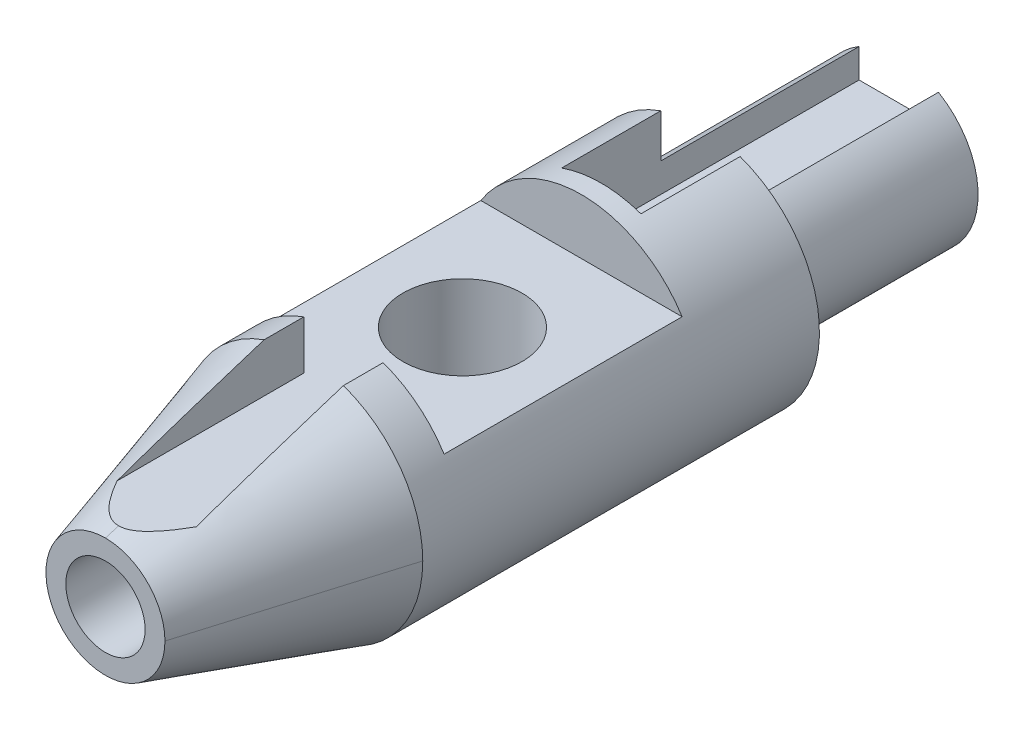
SolidWorks part; units mm, degrees
ref_plane "Front Plane" through (0, 0, 0) normal (0, 0, 1) x (1, 0, 0)
ref_plane "Top Plane" through (0, 0, 0) normal (0, 1, 0) x (1, 0, 0)
ref_plane "Right Plane" through (0, 0, 0) normal (1, 0, 0) x (0, 0, -1)
sketch "Sketch2" plane through (0, 0, 0) normal (0, 0, 1) x (1, 0, 0)
  circle A0 centre (0, 0) radius 30
  dimension "D1" = 60
extrude "Boss-Extrude1" add sketch "Sketch2" against normal blind 50
sketch "Sketch4" plane through (0, 0, -50) normal (0, 0, -1) x (-1, 0, 0)
  circle A0 centre (0, 0) radius 30
  dimension "D1" = 60
extrude "Boss-Extrude4" add sketch "Sketch4" along normal blind 100 contours A0
sketch "Sketch8" plane through (0, 0, -150) normal (0, 0, -1) x (-1, 0, 0)
  circle A1 centre (0, 0) radius 20
  dimension "D2" = 40
sketch "Sketch11" plane through (0, 0, 0) normal (1, 0, 0) x (0, 0, -1)
  line L0 (0, 15) -> (50, 30)
  line L1 (0, 30) -> (0, -30) construction
  line L2 (50, 30) -> (0, 30)
  line L3 (0, 30) -> (0, 15)
  line L4 (150, 30) -> (0, 30) construction
  line L5 (-75, 0) -> (75, 0) construction
  dimension "D1" = 15
  dimension "D2" = 50
  dimension "D3" = 150
sweep "Cut-Sweep1" cut profiles "Sketch11" path edge at (30, 0, 0)
sketch "Sketch20" plane through (0, 0, 0) normal (1, 0, 0) x (0, 0, -1)
  line L0 (60, 30) -> (60, 16)
  line L1 (150, 30) -> (50, 30) construction
  line L2 (60, 16) -> (120, 16)
  line L3 (120, 16) -> (120, 30)
  line L4 (120, 30) -> (60, 30)
  line L5 (50, 30) -> (50, 0) construction
  line L6 (70, -30) -> (110, -30)
  line L7 (50, -30) -> (150, -30) construction
  line L8 (110, -30) -> (110, -20)
  line L9 (110, -20) -> (70, -20)
  line L10 (70, -20) -> (70, -30)
  line L11 (50, -30) -> (50, 30) construction
  dimension "D1" = 60
  dimension "D2" = 10
  dimension "D3" = 14
  dimension "D4" = 40
  dimension "D5" = 20
  dimension "D6" = 10
extrude "Cut-Extrude3" cut sketch "Sketch20" against normal up to next and the other way up to next contours L4 L0 L2 L3 | L10 L6 L8 L9
extrude "Boss-Extrude6" add sketch "Sketch8" along normal blind 50
sketch "Sketch22" plane through (0, 16, 0) normal (0, 1, 0) x (1, 0, 0)
  line L0 (-10, 60) -> (-10, 0)
  line L1 (-10, 0) -> (10, 0)
  line L2 (10, 0) -> (10, 60)
  line L3 (10, 60) -> (-10, 60)
  line L9 (25.3772, 60) -> (-25.3772, 60) construction
  dimension "D1" = 20
  dimension "D2" = 10
extrude "Cut-Extrude14" cut sketch "Sketch22" along normal up to next contours L0 L1 L2 L3
sketch3d "3DSketch1"
  point P4 (0, 10, 0)
  point P13 (0, 10, -200)
ref_plane "Plane3" through (0, 10, 0) normal (0, 1, 0) x (1, 0, 0)
sketch "Sketch23" plane through (0, 10, 0) normal (0, 1, 0) x (1, 0, 0)
  line L0 (-10, 200) -> (10, 200)
  line L1 (20, 200) -> (-20, 200) construction
  line L2 (10, 200) -> (10, 125)
  line L3 (10, 125) -> (-10, 125)
  line L4 (-10, 125) -> (-10, 200)
  line L5 (0, 0) -> (0, 3.3333) construction
  dimension "D1" = 20
  dimension "D2" = 75
  dimension "D3" = 10
extrude "Cut-Extrude16" cut sketch "Sketch23" along normal up to next
hole_wizard "V (0.377) Diameter Hole2" positions "Sketch24" profile "Sketch25" hole size "V" standard "ANSI Inch"
sketch "Sketch24" plane through (0, 0, 0) normal (0, 0, 1) x (1, 0, 0)
  point P0 (0, 0)
sketch "Sketch25" plane through (0, 0, 0) normal (1, 0, 0) x (0, -1, 0)
  line L0 (0, 0) -> (0, 67.3205)
  line L1 (0, 67.3205) -> (10, 30)
  line L2 (10, 30) -> (10, 0)
  line L5 (10, 0) -> (0, 0)
  line L10 (0, 67.3205) -> (-10, 30) construction
  line L11 (0, -6.35) -> (0, 107.95) construction
  dimension "Hole Dia." = 20
  dimension "Hole Depth" = 30
  dimension "Drill Angle" = 30
sketch "Sketch26" plane through (0, 16, 0) normal (0, 1, 0) x (1, 0, 0)
  line L0 (10, 50) -> (30, 50) construction
  circle A0 centre (0, 90) radius 15
  point P5 (0, 0)
  dimension "D1" = 30
  dimension "D2" = 40
extrude "Cut-Extrude17" cut sketch "Sketch26" against normal up to next
